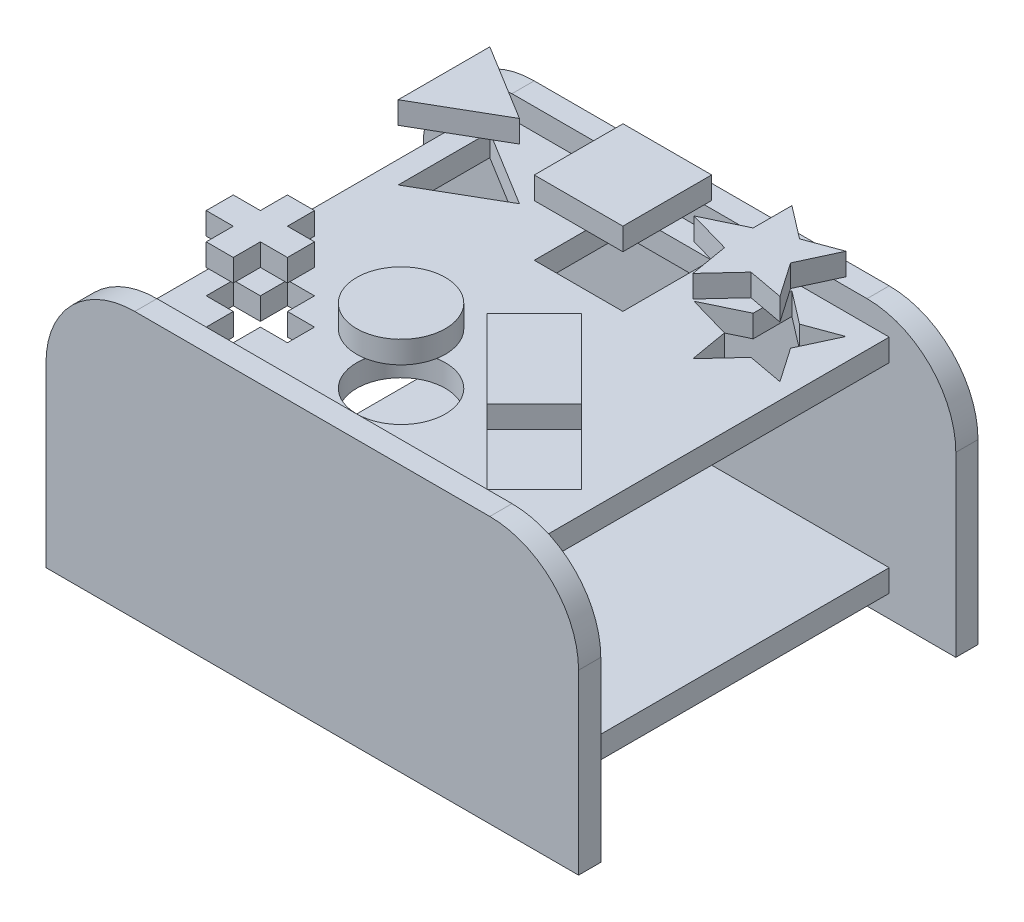
SolidWorks part; units mm, degrees
ref_plane "Front Plane" through (0, 0, 0) normal (0, 0, 1) x (1, 0, 0)
ref_plane "Top Plane" through (0, 0, 0) normal (0, 1, 0) x (1, 0, 0)
ref_plane "Right Plane" through (0, 0, 0) normal (1, 0, 0) x (0, 0, -1)
sketch "Sketch1" plane through (0, 0, 0) normal (0, 0, 1) x (1, 0, 0)
  line L1 (0, 0) -> (304.8, 0)
  line L2 (0, 0) -> (0, 152.4)
  line L3 (0, 152.4) -> (304.8, 152.4)
  line L4 (304.8, 0) -> (304.8, 152.4)
  dimension "D1" = 304.8
  dimension "D2" = 152.4
extrude "Boss-Extrude1" add sketch "Sketch1" along normal blind 12.7
fillet "Fillet3" radius 50.8 2 edges at (0, 152.4, 6.35) (304.8, 152.4, 6.35)
sketch "Sketch2" plane through (0, 0, 12.7) normal (0, 0, 1) x (1, 0, 0)
  line L0 (254, 152.4) -> (50.8, 152.4) construction
  line L1 (38.1, 139.7) -> (266.7, 139.7)
  line L2 (38.1, 139.7) -> (38.1, 127)
  line L3 (38.1, 127) -> (266.7, 127)
  line L4 (266.7, 139.7) -> (266.7, 127)
  line L5 (304.8, 0) -> (304.8, 101.6) construction
  line L6 (0, 101.6) -> (0, 0) construction
  dimension "D1" = 12.7
  dimension "D2" = 38.1
  dimension "D3" = 12.7
  dimension "D4" = 38.1
extrude "Boss-Extrude2" add sketch "Sketch2" along normal blind 203.2
sketch "Sketch3" plane through (0, 0, 215.9) normal (0, 0, 1) x (1, 0, 0)
  line L1 (0, 0) -> (304.8, 0)
  line L2 (0, 0) -> (0, 152.4)
  line L3 (0, 152.4) -> (304.8, 152.4)
  line L4 (304.8, 0) -> (304.8, 152.4)
  dimension "D1" = 304.8
  dimension "D2" = 152.4
extrude "Boss-Extrude3" add sketch "Sketch3" along normal blind 12.7
fillet "Fillet4" radius 50.8 2 edges at (304.8, 152.4, 222.25) (0, 152.4, 222.25)
sketch "Sketch4" [suppressed] plane through (0, 0, 12.7) normal (0, 0, 1) x (1, 0, 0)
  line L0 (0, 0) -> (304.8, 0) construction
  line L1 (12.7, 12.7) -> (266.7, 12.7)
  line L2 (12.7, 12.7) -> (12.7, 25.4)
  line L3 (12.7, 25.4) -> (266.7, 25.4)
  line L4 (266.7, 12.7) -> (266.7, 25.4)
  line L5 (304.8, 0) -> (304.8, 101.6) construction
  line L6 (0, 101.6) -> (0, 0) construction
  dimension "D1" = 12.7
  dimension "D2" = 38.1
  dimension "D3" = 12.7
  dimension "D4" = 12.7
extrude "Boss-Extrude4" [suppressed] add sketch "Sketch4" along normal blind 203.2
sketch "Sketch5" plane through (0, 0, 12.7) normal (0, 0, 1) x (1, 0, 0)
  line L0 (0, 0) -> (304.8, 0) construction
  line L1 (38.1, 25.4) -> (266.7, 25.4)
  line L2 (38.1, 25.4) -> (38.1, 12.7)
  line L3 (38.1, 12.7) -> (266.7, 12.7)
  line L4 (266.7, 25.4) -> (266.7, 12.7)
  line L5 (304.8, 0) -> (304.8, 101.6) construction
  line L6 (0, 101.6) -> (0, 0) construction
  dimension "D1" = 12.7
  dimension "D2" = 12.7
  dimension "D3" = 38.1
  dimension "D4" = 38.1
extrude "Boss-Extrude5" add sketch "Sketch5" along normal blind 203.2
sketch "Sketch6" plane through (0, 139.7, 0) normal (0, 1, 0) x (1, 0, 0)
  line L0 (254, -215.9) -> (50.8, -215.9) construction
  line L1 (38.1, -215.9) -> (38.1, -12.7) construction
  line L2 (127.0476, -76.2) -> (152.4, -76.2)
  line L4 (177.7524, -25.4) -> (127.0476, -25.4)
  line L5 (177.7524, -25.4) -> (177.7524, -76.2)
  line L6 (177.7524, -76.2) -> (127.0476, -76.2)
  line L7 (127.0476, -25.4) -> (127.0476, -76.2)
  line L8 (177.7524, -25.4) -> (177.7524, -50.8)
  line L9 (266.7, -12.7) -> (38.1, -12.7) construction
  circle A0 centre (152.4, -177.8) radius 25.4
  point P4 (152.4, -215.9)
  dimension "D1" = 38.1
  dimension "D2" = 114.3
  dimension "D3" = 50.8
  dimension "D4" = 114.3
  dimension "D5" = 38.1
extrude "Cut-Extrude1" cut sketch "Sketch6" against normal blind 50.8 contours A0 | L4 L7 L2 L6 L5
sketch "Sketch7" plane through (0, 139.7, 0) normal (0, 1, 0) x (1, 0, 0)
  line L0 (50.8, -25.4) -> (50.8, -77.8249)
  line L1 (50.8, -77.8249) -> (94.7941, -52.4249)
  line L2 (94.7941, -52.4249) -> (50.8, -25.4)
  line L3 (38.1, -215.9) -> (38.1, -12.7) construction
  line L4 (266.7, -12.7) -> (38.1, -12.7) construction
  dimension "D1" = 12.7
  dimension "D2" = 12.7
extrude "Cut-Extrude2" cut sketch "Sketch7" against normal blind 50.8
sketch "Sketch8" plane through (0, 139.7, 0) normal (0, 1, 0) x (1, 0, 0)
  line L0 (50.8, -172.212) -> (50.8, -187.706)
  line L1 (50.8, -187.706) -> (66.294, -187.706)
  line L2 (66.294, -187.706) -> (66.294, -203.2)
  line L3 (66.294, -203.2) -> (81.788, -203.2)
  line L4 (81.788, -203.2) -> (81.788, -187.706)
  line L5 (81.788, -187.706) -> (97.282, -187.706)
  line L6 (97.282, -187.706) -> (97.282, -172.212)
  line L7 (97.282, -172.212) -> (81.788, -172.212)
  line L8 (81.788, -172.212) -> (81.788, -156.718)
  line L9 (81.788, -156.718) -> (66.294, -156.718)
  line L10 (66.294, -156.718) -> (66.294, -172.212)
  line L11 (66.294, -172.212) -> (50.8, -172.212)
  line L12 (38.1, -215.9) -> (38.1, -12.7) construction
  line L13 (50.8, -187.706) -> (50.8, -179.959)
  line L15 (266.7, -215.9) -> (38.1, -215.9) construction
  dimension "D1" = 12.7
  dimension "D2" = 15.494
  dimension "D3" = 12.7
  dimension "D4" = 15.494
  dimension "D5" = 15.494
  dimension "D6" = 15.494
  dimension "D7" = 15.494
  dimension "D8" = 15.494
  dimension "D9" = 15.494
  dimension "D10" = 15.494
  dimension "D11" = 15.494
  dimension "D12" = 15.494
extrude "Cut-Extrude3" cut sketch "Sketch8" against normal blind 50.8 contours L10 L11 L0 L1 L2 L3 L4 L5 L6 L7 L8 L9
sketch "Sketch10" plane through (0, 139.7, 0) normal (0, 1, 0) x (1, 0, 0)
  line L0 (254, -176.2592) -> (227.0592, -203.2)
  line L1 (227.0592, -203.2) -> (182.158, -158.2987)
  line L2 (182.158, -158.2987) -> (209.0987, -131.358)
  line L3 (209.0987, -131.358) -> (254, -176.2592)
extrude "Cut-Extrude5" cut sketch "Sketch10" against normal blind 50.8
sketch "Sketch11" plane through (0, 139.7, 0) normal (0, 1, 0) x (1, 0, 0)
  line L0 (193.0359, -50.8) -> (243.9644, -46.447)
  line L1 (193.0359, -50.8) -> (215.9347, -39.8088)
  line L2 (215.9347, -39.8088) -> (215.9347, -17.6439)
  line L3 (215.9347, -17.6439) -> (234.6006, -31.9478)
  line L4 (234.6006, -31.9478) -> (254, -24.7959)
  line L5 (254, -24.7959) -> (243.9644, -46.447)
  line L6 (257.5287, -66.081) -> (243.9644, -46.447)
  line L7 (237.197, -62.325) -> (257.5287, -66.081)
  line L8 (221.2293, -79.5891) -> (237.197, -62.325)
  line L9 (217.4678, -57.7457) -> (221.2293, -79.5891)
  line L10 (193.0359, -50.8) -> (217.4678, -57.7457)
  line L14 (177.7524, -25.4) -> (177.7524, -50.8)
  line L15 (177.7524, -25.4) -> (177.7524, -76.2) construction
extrude "Cut-Extrude7" cut sketch "Sketch11" against normal blind 50.8 contours L0 L10 L9 L8 L7 L6 | L5 L4 L3 L2 L1 L0
sketch "Sketch16" plane through (0, 139.7, 0) normal (0, 1, 0) x (1, 0, 0)
  line L0 (193.0359, -50.8) -> (217.4678, -57.7457)
  line L1 (217.4678, -57.7457) -> (221.2293, -79.5891)
  line L2 (221.2293, -79.5891) -> (237.197, -62.325)
  line L3 (237.197, -62.325) -> (257.5287, -66.081)
  line L4 (257.5287, -66.081) -> (243.9644, -46.447)
  line L5 (243.9644, -46.447) -> (254, -24.7959)
  line L6 (254, -24.7959) -> (234.6006, -31.9478)
  line L7 (234.6006, -31.9478) -> (215.9347, -17.6439)
  line L8 (215.9347, -17.6439) -> (215.9347, -39.8088)
  line L9 (215.9347, -39.8088) -> (193.0359, -50.8)
sketch "Sketch17" plane through (0, 169.2652, 0) normal (0, 1, 0) x (1, 0, 0)
  line L0 (50.8, -25.4) -> (50.8, -77.8249)
  line L1 (50.8, -77.8249) -> (94.7941, -52.4249)
  line L2 (94.7941, -52.4249) -> (50.8, -25.4)
  line L3 (66.294, -156.718) -> (81.788, -156.718)
  line L4 (81.788, -156.718) -> (81.788, -172.212)
  line L5 (81.788, -172.212) -> (97.282, -172.212)
  line L6 (97.282, -172.212) -> (97.282, -187.706)
  line L7 (97.282, -187.706) -> (81.788, -187.706)
  line L8 (81.788, -187.706) -> (81.788, -203.2)
  line L9 (81.788, -203.2) -> (66.294, -203.2)
  line L10 (66.294, -203.2) -> (66.294, -187.706)
  line L11 (66.294, -187.706) -> (50.8, -187.706)
  line L12 (50.8, -187.706) -> (50.8, -172.212)
  line L13 (50.8, -172.212) -> (66.294, -172.212)
  line L14 (66.294, -172.212) -> (66.294, -156.718)
  line L15 (182.158, -158.2987) -> (209.0987, -131.358)
  line L16 (127.0476, -25.4) -> (177.7524, -25.4)
  line L17 (127.0476, -25.4) -> (127.0476, -76.2)
  line L18 (127.0476, -76.2) -> (177.7524, -76.2)
  line L19 (177.7524, -25.4) -> (177.7524, -76.2)
  line L20 (209.0987, -131.358) -> (254, -176.2592)
  line L21 (254, -176.2592) -> (227.0592, -203.2)
  line L22 (227.0592, -203.2) -> (182.158, -158.2987)
  line L23 (193.0359, -50.8) -> (215.9347, -39.8088)
  line L24 (215.9347, -39.8088) -> (215.9347, -17.6439)
  line L25 (215.9347, -17.6439) -> (234.6006, -31.9478)
  line L26 (234.6006, -31.9478) -> (254, -24.7959)
  line L27 (254, -24.7959) -> (243.9644, -46.447)
  line L28 (243.9644, -46.447) -> (257.5287, -66.081)
  line L29 (257.5287, -66.081) -> (237.197, -62.325)
  line L30 (237.197, -62.325) -> (221.2293, -79.5891)
  line L31 (217.4678, -57.7457) -> (221.2293, -79.5891) construction
  line L32 (221.2293, -79.5891) -> (237.197, -62.325) construction
  line L33 (221.2293, -79.5891) -> (217.4678, -57.7457)
  line L34 (217.4678, -57.7457) -> (193.0359, -50.8)
  circle A0 centre (152.4, -177.8) radius 25.4
extrude "Boss-Extrude9" add sketch "Sketch17" along normal blind 12.7
